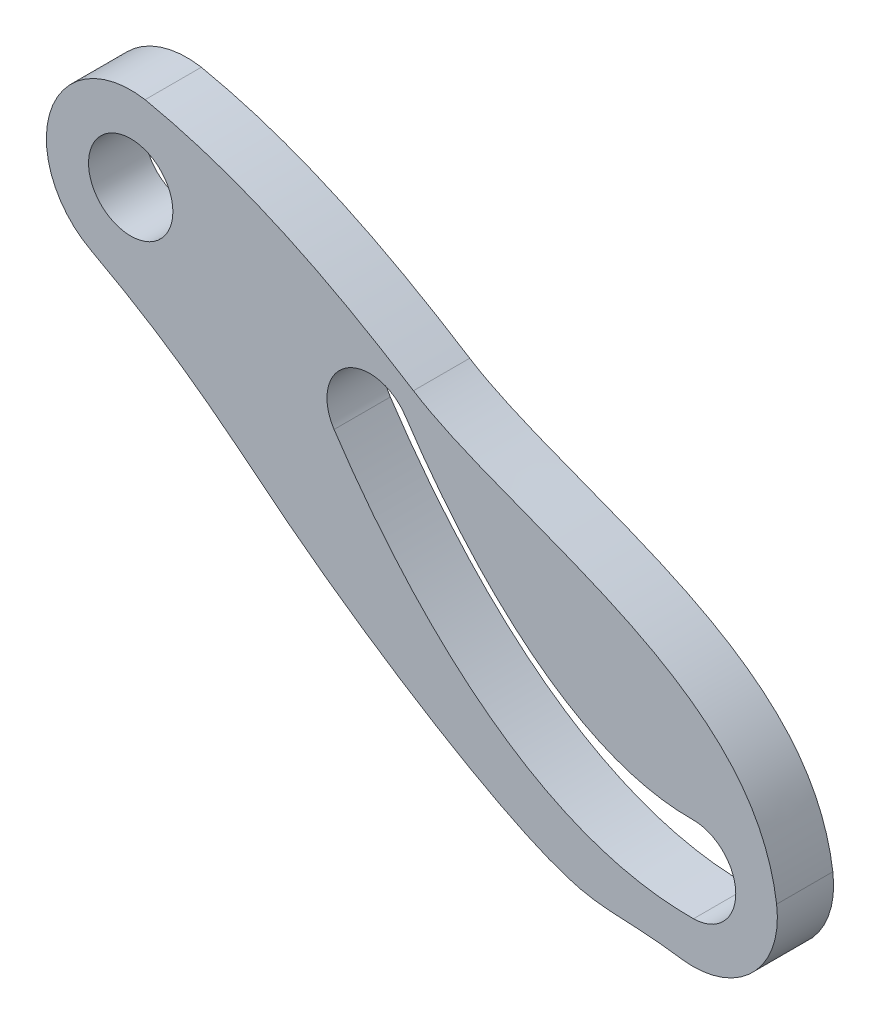
SolidWorks part; units mm, degrees
ref_plane "前视基准面" through (0, 0, 0) normal (0, 0, 1) x (1, 0, 0)
ref_plane "上视基准面" through (0, 0, 0) normal (0, 1, 0) x (1, 0, 0)
ref_plane "右视基准面" through (0, 0, 0) normal (1, 0, 0) x (0, 0, -1)
sketch "草图1" plane through (0, 0, 0) normal (0, 0, 1) x (1, 0, 0)
  circle A0 centre (0, 0) radius 1.52
  circle A1 centre (11.5, -8) radius 1.52
  arc A2 (-7.9879, 5.956) -> (-9.9199, 0.3573) centre (-8.5, 3) ccw
  circle A3 centre (-8.5, 3) radius 1.5
  arc A5 (11.0808, -10.9706) -> (12.0999, -5.0606) centre (11.5, -8) ccw
  spline S0 degree 3 poles (0, 0) (2.5058, -3.7737) (6.5604, -8.0579) (11.5, -8) knots 0 0 0 0 1 1 1 1
  spline S1 degree 1 poles (-1.2663, -0.8408) (11.5178, -9.5199) knots 0 0 1 1 construction
  spline S2 degree 3 poles (-1.2663, -0.8408) (-0.9267, -1.3522) (-0.2332, -2.3371) (1.3955, -4.3649) (3.7894, -6.7414) (6.7126, -8.5594) (9.3582, -9.3848) (10.8051, -9.5282) (11.5178, -9.5199) knots 0 0 0 0 0.125 0.25 0.5 0.75 0.875 1 1 1 1
  spline S3 degree 1 poles (1.2663, 0.8408) (11.4822, -6.4801) knots 0 0 1 1 construction
  spline S4 degree 3 poles (1.2663, 0.8408) (1.5724, 0.3798) (2.2006, -0.512) (3.6515, -2.3183) (5.7312, -4.3694) (8.5158, -6.0783) (10.4836, -6.4918) (11.4822, -6.4801) knots 0 0 0 0 0.125 0.25 0.5 0.75 1 1 1 1
  spline S5 degree 3 poles (-7.9879, 5.956) (-3.7438, 6.0728) (1.9645, 2.6064) (9.9711, -1.6437) (11.2815, -4.9155) (12.0999, -5.0606) knots 0 0 0 0 0.49205 0.916773 1 1 1 1
  spline S6 degree 3 poles (-9.9199, 0.3573) (-6.2145, -1.6335) (-3.2078, -4.7772) (7.0781, -11.2735) (9.127, -10.6948) (11.0808, -10.9706) knots 0 0 0 0 0.359134 0.783116 1 1 1 1
  point P13 (3.01, 4.02)
  dimension "D1" = 8
  dimension "D2" = 11.5
  dimension "D3" = 3.04
  dimension "D4" = 3.04
  dimension "D7" = 8.5
  dimension "D9" = 11.51
  dimension "D10" = 6
  dimension "D11" = 3
  dimension "D12" = 3
  dimension "D13" = 3
  dimension "D8" = 1.02
  dimension "D5" = 1.52
  dimension "D6" = 1.52
extrude "凸台-拉伸1" add sketch "草图1" along normal blind 2
sketch "草图2" plane through (0, 0, 2) normal (0, 0, 1) x (1, 0, 0)
  arc A0 (11.0808, -10.9706) -> (12.0999, -5.0606) centre (11.5, -8) ccw construction
  arc A4 (-7.9879, 5.956) -> (-9.9199, 0.3573) centre (-8.5, 3) ccw
  arc A7 (11.0808, -10.9706) -> (12.0999, -5.0606) centre (11.5, -8) ccw
  arc A9 (12.382, -5.1326) -> (12.0999, -5.0606) centre (11.5, -8) ccw
  spline S0 degree 3 poles (10.3748, -3.2486) (10.6638, -3.6487) (11.8989, -4.984) (12.382, -5.1326) knots 0 0 0 0 1 1 1 1
  spline S1 degree 3 poles (-7.9879, 5.956) (-3.7438, 6.0728) (1.9645, 2.6064) (9.9711, -1.6437) (11.2815, -4.9155) (12.0999, -5.0606) knots 0 0 0 0 0.49205 0.916773 1 1 1 1 construction
  spline S4 degree 3 poles (-970.7675, 277.4331) (13.5177, 1.3378) (-24.6375, 8.757) (23.0673, -21.3717) (-7.6627, 20.0106) (902.9793, -463.1541) knots -2.083404 -2.083404 -2.083404 -2.083404 0.359134 0.783116 2.554474 2.554474 2.554474 2.554474 only from (-9.9199, 0.3573) to (11.0808, -10.9706)
  spline S5 degree 3 poles (2568.6559, 1564.1229) (1.6861, -27.0392) (19.7348, -6.8265) (-36.3036, 22.9199) (-18.9087, 30.5322) (-1978.354, -2255.9303) knots -1.219453 -1.219453 -1.219453 -1.219453 0.083227 0.50795 5.779566 5.779566 5.779566 5.779566 only from (12.0999, -5.0606) to (-7.9879, 5.956)
  spline S7 degree 3 poles (12.0999, -5.0606) (11.2815, -4.9155) (10.9763, -4.1534) (10.5215, -3.4517) (10.3748, -3.2486) knots 0 0 0 0 0.083227 0.118311 0.118311 0.118311 0.118311
  dimension "D1" = 0
extrude "凸台-拉伸2" add sketch "草图2" against normal blind 2
sketch "草图7" plane through (0, 0, 2) normal (0, 0, 1) x (1, 0, 0)
  line L0 (-7.9879, 5.956) -> (1.2661, 11.163)
  line L1 (1.2661, 11.163) -> (12.382, -5.1326)
  spline S0 degree 3 poles (-7.9879, 5.956) (-0.0778, 4.3108) (5.4521, -1.6165) (12.382, -5.1326) knots 0 0 0 0 1 1 1 1
extrude "切除-拉伸6" cut sketch "草图7" against normal blind 10
sketch "草图8" plane through (0, 0, 2) normal (0, 0, 1) x (1, 0, 0)
  arc A0 (11.0808, -10.9706) -> (12.382, -5.1326) centre (11.5, -8) ccw construction
  arc A3 (-7.9879, 5.956) -> (-9.9199, 0.3573) centre (-8.5, 3) ccw
  arc A4 (11.0808, -10.9706) -> (12.382, -5.1326) centre (11.5, -8) ccw
  arc A6 (14.4726, -7.5952) -> (12.382, -5.1326) centre (11.5, -8) ccw
  spline S0 degree 3 poles (1.5567, 1.7641) (4.4956, -0.0973) (12.1326, -1.3441) (14.3129, -6.4226) (14.4726, -7.5952) knots 0 0 0 0 0.805722 1 1 1 1
  spline S1 degree 3 poles (-7.9879, 5.956) (-0.1647, 4.3289) (5.3303, -1.4869) (12.1543, -5.0159) knots 0 0 0 0 0.989021 0.989021 0.989021 0.989021 construction
  spline S5 degree 3 poles (1629.2983, 2518.8023) (-1428.6094, -2650.8685) (1436.2908, 2652.0024) (-1610.7825, -2527.498) knots -6.961806 -6.961806 -6.961806 -6.961806 7.66719 7.66719 7.66719 7.66719 only from (12.1543, -5.0159) to (-7.9879, 5.956)
  spline S6 degree 3 poles (-970.7675, 277.4331) (13.5177, 1.3378) (-24.6375, 8.757) (23.0673, -21.3717) (-7.6627, 20.0106) (902.9793, -463.1541) knots -2.083404 -2.083404 -2.083404 -2.083404 0.359134 0.783116 2.554474 2.554474 2.554474 2.554474 only from (-9.9199, 0.3573) to (11.0808, -10.9706)
  spline S7 degree 3 poles (-1820.0539, 2370.008) (1902.5894, -2391.9754) (-1906.5537, 2363.4137) (1922.0941, -2318.3053) knots -9.859233 -9.859233 -9.859233 -9.859233 10.889903 10.889903 10.889903 10.889903 only from (12.382, -5.1326) to (12.1543, -5.0159)
  spline S8 degree 3 poles (12.1543, -5.0159) (8.4238, -3.0867) (5.0904, -0.474) (1.5567, 1.7641) knots 0 0 0 0 0.540678 0.540678 0.540678 0.540678
  spline S10 degree 3 poles (12.382, -5.1326) (12.318, -5.1129) (12.2408, -5.0724) (12.1543, -5.0159) knots 0 0 0 0 0.13253 0.13253 0.13253 0.13253
  dimension "D1" = 0
extrude "凸台-拉伸3" add sketch "草图8" against normal blind 2
